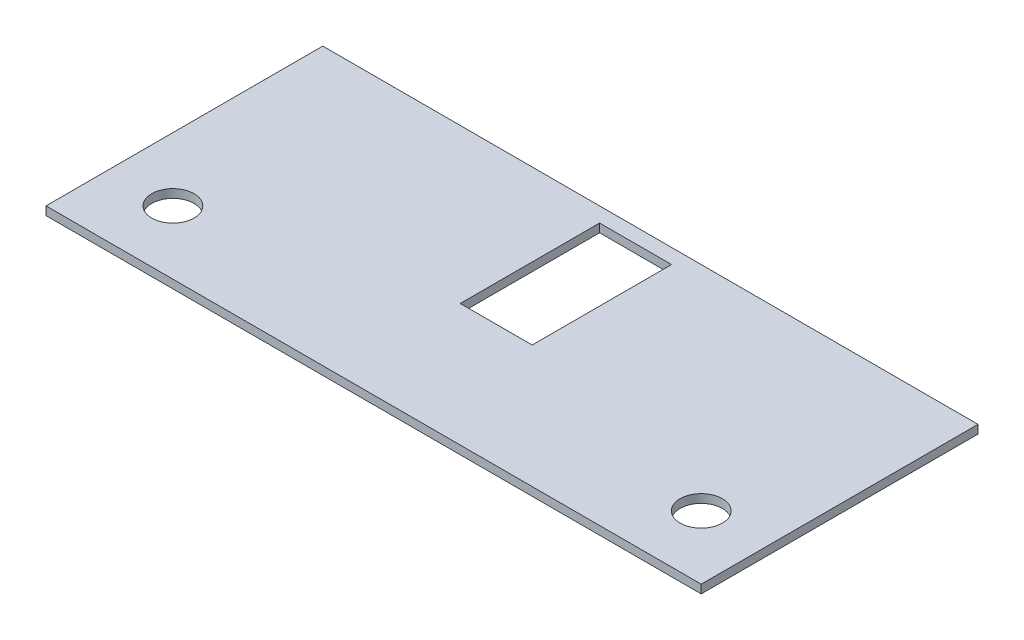
SolidWorks part; units mm, degrees
ref_plane "Спереди" through (0, 0, 0) normal (0, 0, 1) x (1, 0, 0)
ref_plane "Сверху" through (0, 0, 0) normal (0, 1, 0) x (1, 0, 0)
ref_plane "Справа" through (0, 0, 0) normal (1, 0, 0) x (0, 0, -1)
sketch "Эскиз1" plane through (0, 0, 0) normal (0, 1, 0) x (1, 0, 0)
  line L1 (-77.4449, 20.3961) -> (77.4449, 20.3961)
  line L2 (-77.4449, 20.3961) -> (-77.4449, -45.0352)
  line L3 (-77.4449, -45.0352) -> (77.4449, -45.0352)
  line L4 (77.4449, 20.3961) -> (77.4449, -45.0352)
  line L7 (-8.5, 16.8877) -> (8.5, 16.8877)
  line L8 (-8.5, 16.8877) -> (-8.5, -16.0532)
  line L9 (-8.5, -16.0532) -> (8.5, -16.0532)
  line L10 (8.5, 16.8877) -> (8.5, -16.0532)
extrude "Вытянуть1" add sketch "Эскиз1" along normal blind 2
sketch "Эскиз2" plane through (0, 2, 0) normal (0, 1, 0) x (1, 0, 0)
  line L0 (-77.4449, -45.0352) -> (77.4449, -45.0352) construction
  line L1 (-77.4449, 20.3961) -> (-77.4449, -45.0352) construction
  line L2 (0, 20.3961) -> (0, 46.6019) construction
  circle A0 centre (-62.4449, -30.0352) radius 5
  circle A1 centre (62.4449, -30.0352) radius 5
  dimension "D1" = 15
  dimension "D2" = 15
extrude "Вытянуть2" cut sketch "Эскиз2" against normal through all
